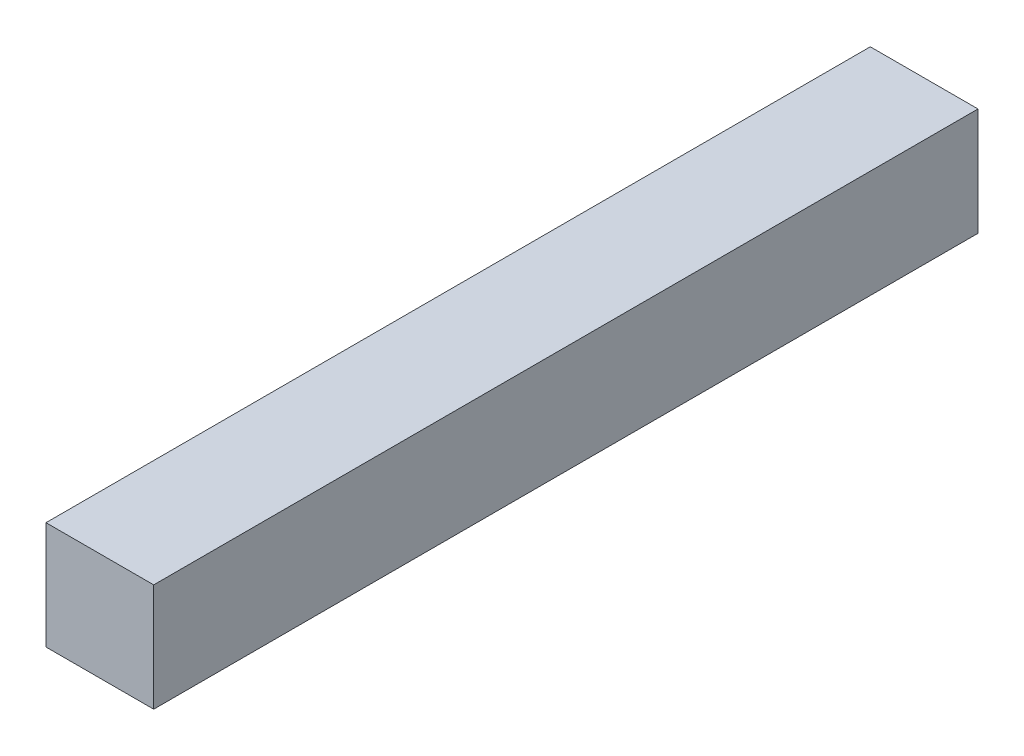
SolidWorks part; units mm, degrees
ref_plane "Front Plane" through (0, 0, 0) normal (0, 0, 1) x (1, 0, 0)
ref_plane "Top Plane" through (0, 0, 0) normal (0, 1, 0) x (1, 0, 0)
ref_plane "Right Plane" through (0, 0, 0) normal (1, 0, 0) x (0, 0, -1)
sketch "Sketch1" plane through (0, 0, 0) normal (0, 1, 0) x (1, 0, 0)
  line L0 (0, 0) -> (0, -306.1317)
  line L1 (0, -306.1317) -> (-40, -306.1317)
  line L2 (-40, -306.1317) -> (-40, 0)
  line L3 (-40, 0) -> (0, 0)
  dimension "D1" = 40
extrude "Boss-Extrude1" add sketch "Sketch1" along normal blind 40
